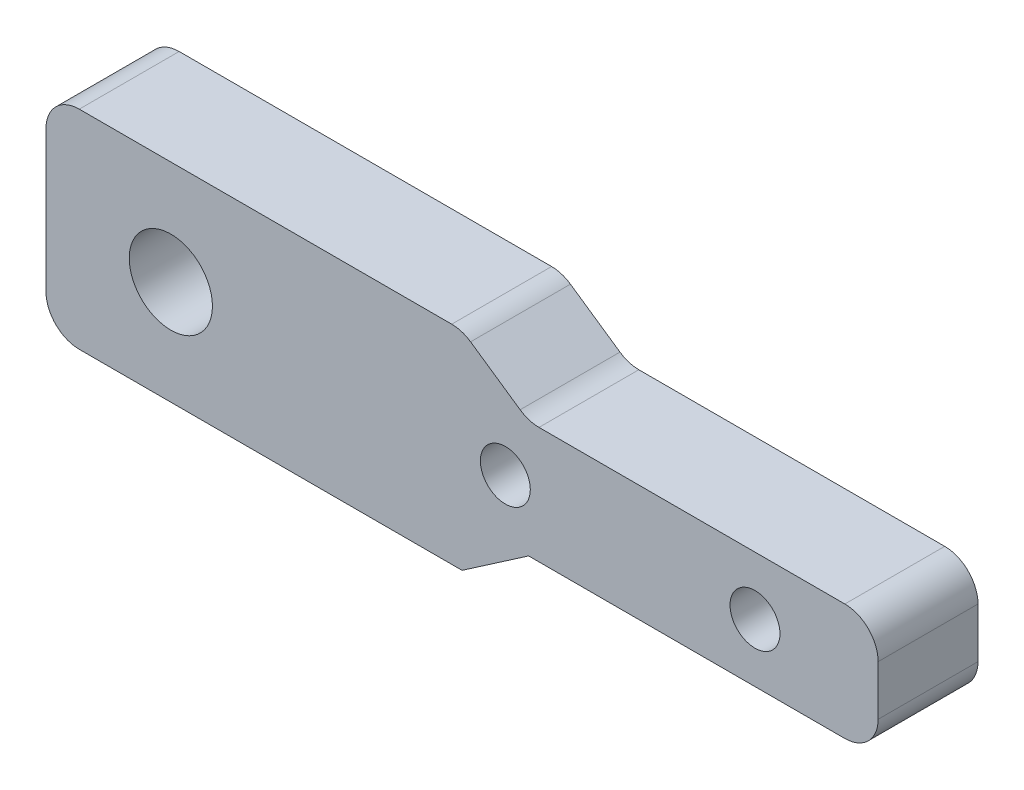
SolidWorks part; units mm, degrees
ref_plane "Plan de face" through (0, 0, 0) normal (0, 0, 1) x (1, 0, 0)
ref_plane "Plan de dessus" through (0, 0, 0) normal (0, 1, 0) x (1, 0, 0)
ref_plane "Plan de droite" through (0, 0, 0) normal (1, 0, 0) x (0, 0, -1)
sketch "Esquisse1" plane through (0, 0, 0) normal (0, 0, 1) x (1, 0, 0)
  line L0 (5.9392, 3.5) -> (26.9392, 3.5)
  line L1 (-23.0608, 6.25) -> (1.9392, 6.25)
  line L2 (-23.0608, 6.25) -> (-23.0608, -6.25)
  line L3 (-23.0608, -6.25) -> (1.9392, -6.25)
  line L4 (26.9392, 3.5) -> (26.9392, -3.5)
  line L5 (-23.0608, 6.25) -> (0, 0) construction
  line L6 (-23.0608, -6.25) -> (0, 0) construction
  line L7 (-23.0608, 0) -> (26.9392, 0) construction
  line L8 (5.9392, -3.5) -> (26.9392, -3.5)
  line L9 (5.9392, 3.5) -> (1.9392, 6.25)
  line L10 (5.9392, -3.5) -> (1.9392, -6.25)
  point P0 (0, 0)
  dimension "D1" = 12.5
  dimension "D2" = 50
  dimension "D3" = 3.5
  dimension "D4" = 4
  dimension "D5" = 25
extrude "Boss.-Extru.1" add sketch "Esquisse1" along normal blind 6
sketch "Esquisse2" plane through (0, 0, 6) normal (0, 0, 1) x (1, 0, 0)
  line L1 (-23.0608, 6.25) -> (-23.0608, -6.25) construction
  line L2 (-23.0608, 0) -> (26.9392, 0) construction
  line L3 (26.9392, -3.5) -> (26.9392, 3.5) construction
  circle A0 centre (-15.5608, 0) radius 2.5
  circle A1 centre (4.5392, 0) radius 1.5
  circle A2 centre (19.5392, 0) radius 1.5
  dimension "D1" = 5
  dimension "D2" = 3
  dimension "D4" = 3
  dimension "D3" = 7.5
  dimension "D5" = 20.1
  dimension "D6" = 35.1
extrude "Enlèv. mat.-Extru.1" cut sketch "Esquisse2" against normal through all
fillet "Congé2" radius 2 6 edges at (26.9392, -3.5, 3) (26.9392, 3.5, 3) (-23.0608, -6.25, 3) (-23.0608, 6.25, 3) (5.9392, 3.5, 3) (1.9392, 6.25, 3)
